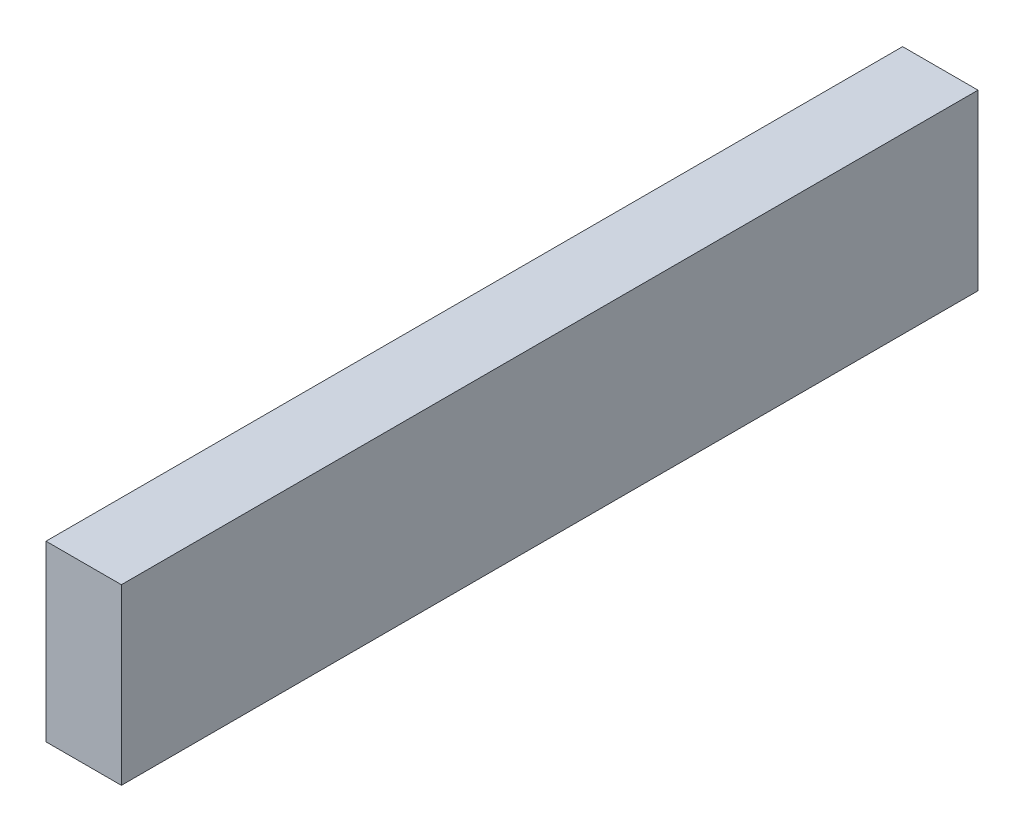
SolidWorks part; units mm, degrees
ref_plane "Front Plane" through (0, 0, 0) normal (1, 0, 0) x (0, 1, 0)
ref_plane "Top Plane" through (0, 0, 0) normal (0, 0, 1) x (0, 1, 0)
ref_plane "Right Plane" through (0, 0, 0) normal (0, 1, 0) x (-1, 0, 0)
sketch "Sketch1" plane through (0, 0, 0) normal (0, 0, 1) x (0, 1, 0)
  line L1 (0, 0) -> (87.6, 0)
  line L2 (0, 0) -> (0, 38)
  line L3 (0, 38) -> (87.6, 38)
  line L4 (87.6, 0) -> (87.6, 38)
  dimension "D1" = 87.6
  dimension "D2" = 38
extrude "Boss-Extrude1" add sketch "Sketch1" along normal blind 431.8
